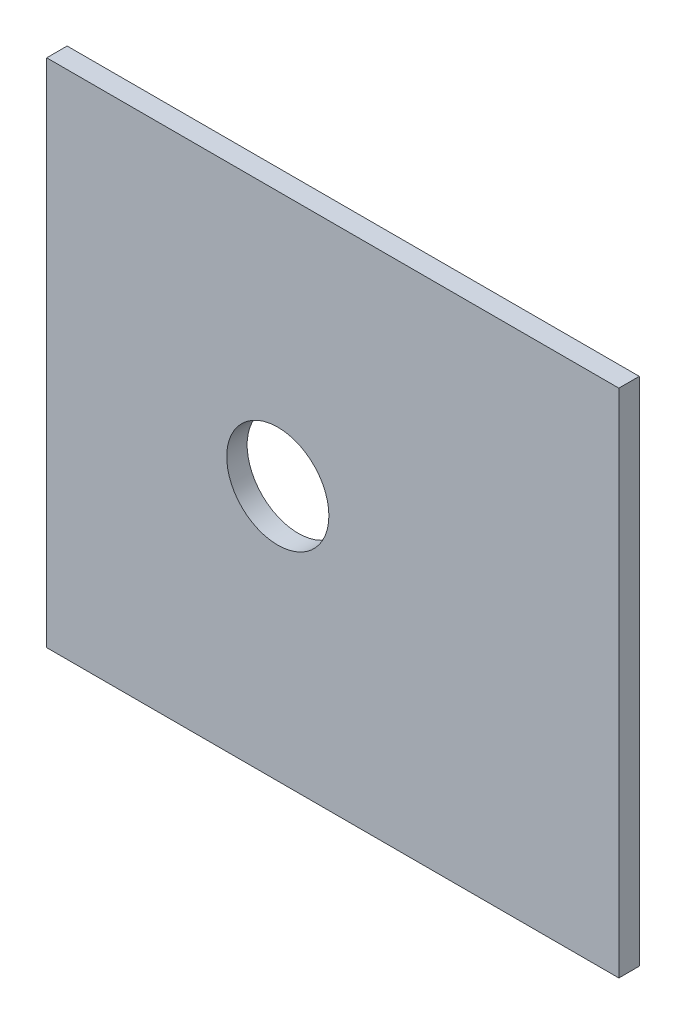
SolidWorks part; units mm, degrees
ref_plane "Front Plane" through (0, 0, 0) normal (0, 0, 1) x (1, 0, 0)
ref_plane "Top Plane" through (0, 0, 0) normal (0, 1, 0) x (1, 0, 0)
ref_plane "Right Plane" through (0, 0, 0) normal (1, 0, 0) x (0, 0, -1)
sketch "Sketch1" plane through (0, 0, 0) normal (0, 0, 1) x (1, 0, 0)
  line L1 (-56, -50) -> (56, -50)
  line L2 (-56, -50) -> (-56, 50)
  line L3 (-56, 50) -> (56, 50)
  line L4 (56, -50) -> (56, 50)
  line L5 (-56, -50) -> (56, 50) construction
  line L6 (-56, 50) -> (56, -50) construction
  circle A0 centre (-10.7634, 0) radius 10
  point P0 (0, 0)
  dimension "D3" = 20
  dimension "D1" = 112
  dimension "D2" = 100
extrude "Boss-Extrude1" add sketch "Sketch1" along normal blind 4
